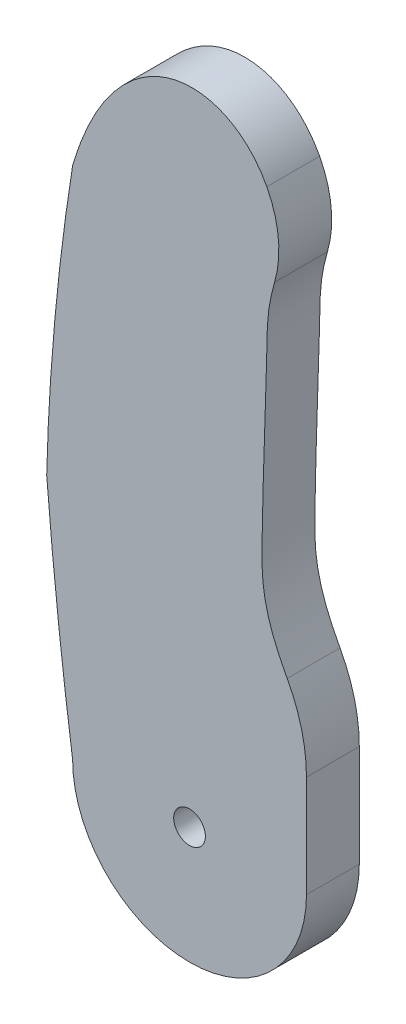
SolidWorks part; units mm, degrees
ref_plane "Front Plane" through (0, 0, 0) normal (0, 0, 1) x (1, 0, 0)
ref_plane "Top Plane" through (0, 0, 0) normal (0, 1, 0) x (1, 0, 0)
ref_plane "Right Plane" through (0, 0, 0) normal (1, 0, 0) x (0, 0, -1)
sketch "Sketch1" plane through (0, 0, 0) normal (0, 0, 1) x (1, 0, 0)
  line L1 (-22.0255, -12.4603) -> (-22.0255, -22.0997)
  arc A0 (-44.1532, -22.0997) -> (-22.0255, -22.0997) centre (-33.0893, -22.0997) ccw
  arc A1 (-25.7774, 34.0422) -> (-25.0423, 26.5822) centre (-34.6362, 29.403) cw
  arc A2 (-23.8518, -5.2872) -> (-22.0255, -12.4603) centre (-37.0255, -12.4603) cw
  spline S0 degree 2 poles (-46.6059, 0) (-46.2587, 13.3745) (-44.1532, 26.5822) knots 0 0 0 1 1 1
  spline S1 degree 3 poles (-44.1532, 26.5822) (-39.9005, 41.1834) (-29.4087, 40.9764) (-25.7774, 34.0422) knots 0 0 0 0 0.860338 0.860338 0.860338 0.860338
  spline S2 degree 3 poles (-25.0423, 26.5822) (-25.76, 24.1412) (-25.7197, 19.5048) (-26.3075, 6.669) (-26.2503, -0.8822) (-23.8518, -5.2872) knots 0.083338 0.083338 0.083338 0.083338 0.311519 0.739397 0.959194 0.959194 0.959194 0.959194
  spline S3 degree 2 poles (-46.6059, 0) (-45.7113, -11.0891) (-44.1532, -22.0997) knots 0 0 0 1 1 1
  dimension "D1" = 10
  dimension "D2" = 15
extrude "Boss-Extrude1" add sketch "Sketch1" along normal blind 5
sketch "Sketch2" plane through (0, 0, 5) normal (0, 0, 1) x (1, 0, 0)
  circle A1 centre (-33.0893, -22.0997) radius 1.5
extrude "Cut-Extrude1" cut sketch "Sketch2" against normal blind 15
